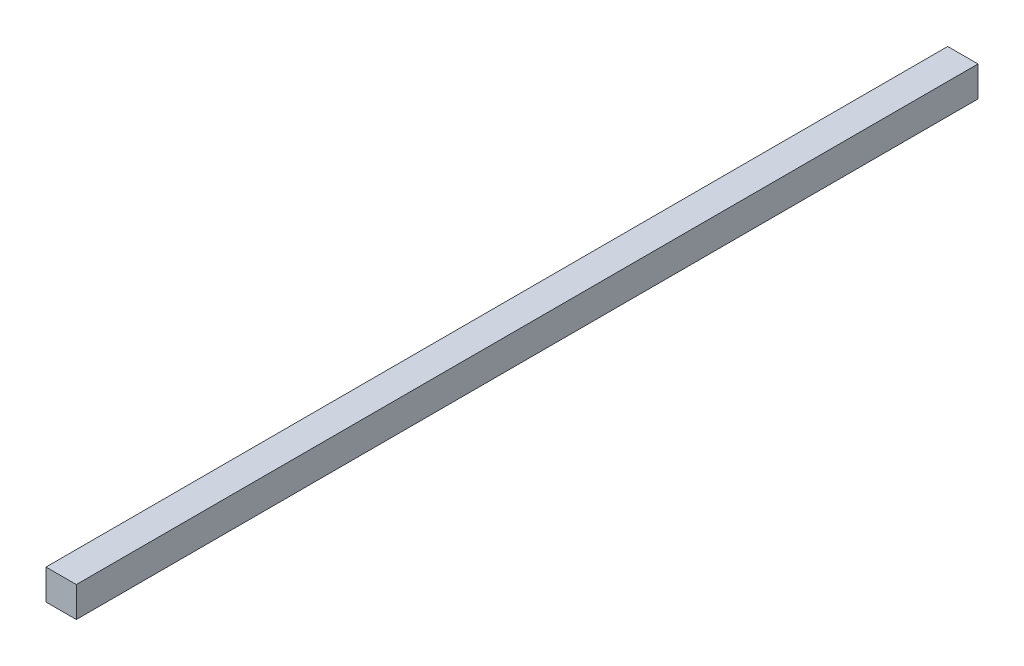
SolidWorks part; units mm, degrees
ref_plane "Front Plane" through (0, 0, 0) normal (0, 0, 1) x (1, 0, 0)
ref_plane "Top Plane" through (0, 0, 0) normal (0, 1, 0) x (1, 0, 0)
ref_plane "Right Plane" through (0, 0, 0) normal (1, 0, 0) x (0, 0, -1)
sketch "Sketch1" plane through (0, 0, 0) normal (0, 0, 1) x (1, 0, 0)
  line L1 (-10, -10) -> (10, -10)
  line L2 (-10, -10) -> (-10, 10)
  line L3 (-10, 10) -> (10, 10)
  line L4 (10, -10) -> (10, 10)
  line L5 (-10, -10) -> (10, 10) construction
  line L6 (-10, 10) -> (10, -10) construction
  point P0 (0, 0)
  dimension "D1" = 20
  dimension "D2" = 20
extrude "Boss-Extrude1" add sketch "Sketch1" along normal blind 595
